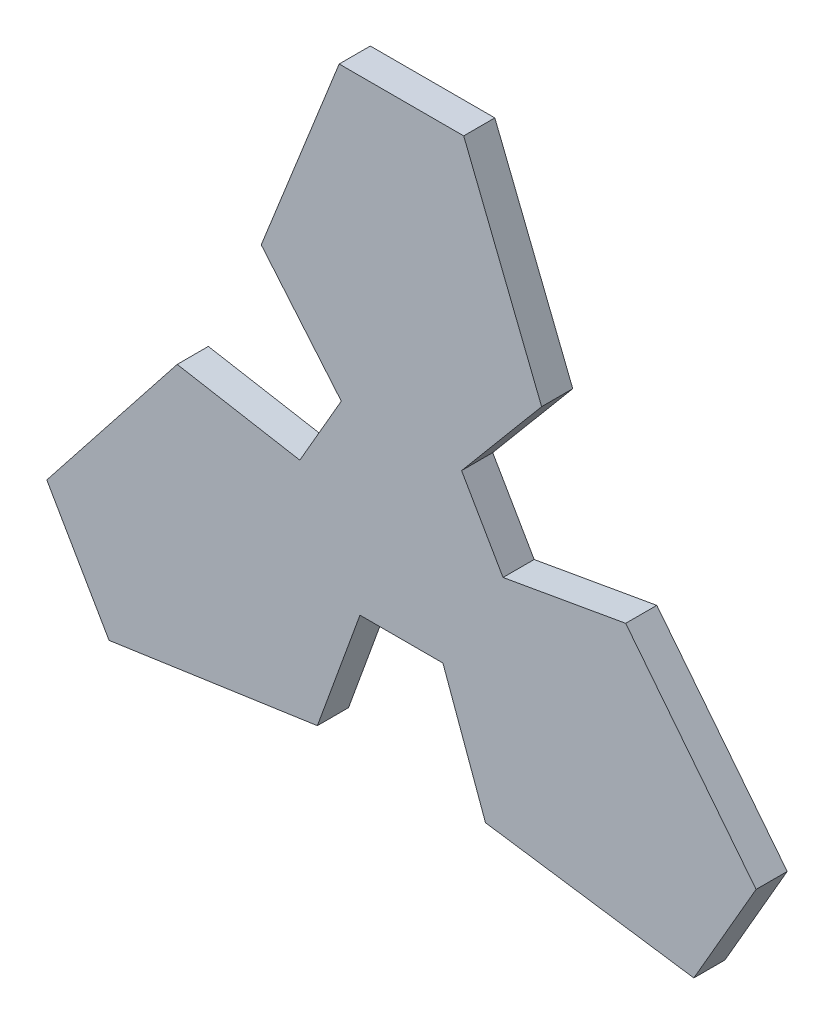
SolidWorks part; units mm, degrees
ref_plane "Front Plane" through (0, 0, 0) normal (0, 0, 1) x (1, 0, 0)
ref_plane "Top Plane" through (0, 0, 0) normal (0, 1, 0) x (1, 0, 0)
ref_plane "Right Plane" through (0, 0, 0) normal (1, 0, 0) x (0, 0, -1)
sketch "Sketch1" plane through (0, 0, 0) normal (0, 0, 1) x (1, 0, 0)
  line L0 (0, 15) -> (0, 60) construction
  line L1 (12.9904, 7.5) -> (8.6603, 15) construction
  line L2 (0, 15) -> (-8.6603, 15) construction
  line L3 (-12.9904, 7.5) -> (-17.3205, 0) construction
  line L4 (-17.3205, 0) -> (-12.9904, -7.5) construction
  line L5 (-8.6603, -15) -> (0, -15) construction
  line L6 (12.9904, -7.5) -> (17.3205, 0) construction
  line L7 (69.282, 0) -> (34.641, 60) construction
  line L8 (34.641, 60) -> (-34.641, 60) construction
  line L9 (-34.641, 60) -> (-69.282, 0) construction
  line L10 (-69.282, 0) -> (-34.641, -60) construction
  line L11 (-34.641, -60) -> (34.641, -60) construction
  line L12 (34.641, -60) -> (69.282, 0) construction
  line L14 (-22.516, 28.5888) -> (-10, 60)
  line L18 (8.6603, 15) -> (0, 15) construction
  line L19 (-12.9904, -7.5) -> (-8.6603, -15) construction
  line L20 (8.6603, -15) -> (12.9904, -7.5) construction
  line L21 (-8.6603, 15) -> (-12.9904, 7.5) construction
  line L22 (17.3205, 0) -> (12.9904, 7.5) construction
  line L23 (0, -15) -> (8.6603, -15) construction
  line L24 (-8.6603, 15) -> (-9.6603, 13.2679) construction
  line L25 (-12.9904, 7.5) -> (-9.6603, 13.2679)
  line L26 (-9.6603, 13.2679) -> (-22.516, 28.5888)
  line L27 (10, 60) -> (-10, 60)
  line L28 (22.516, 28.5888) -> (10, 60)
  line L29 (9.6603, 13.2679) -> (22.516, 28.5888)
  line L30 (12.9904, 7.5) -> (9.6603, 13.2679)
  line L31 (12.9904, 7.5) -> (16.3205, 1.7321)
  line L32 (16.3205, 1.7321) -> (36.0167, 5.205)
  line L33 (36.0167, 5.205) -> (56.9615, -21.3397)
  line L34 (46.9615, -38.6603) -> (56.9615, -21.3397)
  line L35 (13.5007, -33.7939) -> (46.9615, -38.6603)
  line L36 (6.6603, -15) -> (13.5007, -33.7939)
  line L37 (0, -15) -> (6.6603, -15)
  line L38 (0, -15) -> (-6.6603, -15)
  line L39 (-6.6603, -15) -> (-13.5007, -33.7939)
  line L40 (-13.5007, -33.7939) -> (-46.9615, -38.6603)
  line L41 (-56.9615, -21.3397) -> (-46.9615, -38.6603)
  line L42 (-36.0167, 5.205) -> (-56.9615, -21.3397)
  line L43 (-16.3205, 1.7321) -> (-36.0167, 5.205)
  line L44 (-12.9904, 7.5) -> (-16.3205, 1.7321)
  arc A0 (12.9904, 7.5) -> (0, 15) centre (0, 0) ccw construction
  circle A1 centre (0, 0) radius 60 construction
  arc A2 (12.9904, -7.5) -> (12.9904, 7.5) centre (0, 0) ccw construction
  arc A3 (0, -15) -> (12.9904, -7.5) centre (0, 0) ccw construction
  arc A4 (0, 15) -> (-12.9904, 7.5) centre (0, 0) ccw construction
  arc A5 (-12.9904, -7.5) -> (0, -15) centre (0, 0) ccw construction
  arc A6 (-12.9904, 7.5) -> (-12.9904, -7.5) centre (0, 0) ccw construction
  point P47 (0, 0)
  dimension "D1" = 30
  dimension "D2" = 120
  dimension "D3" = 10
  dimension "D4" = 2
  dimension "D5" = 20
  dimension "D6" = 130
  dimension "D7" = 3
extrude "Boss-Extrude1" add sketch "Sketch1" along normal blind 5
